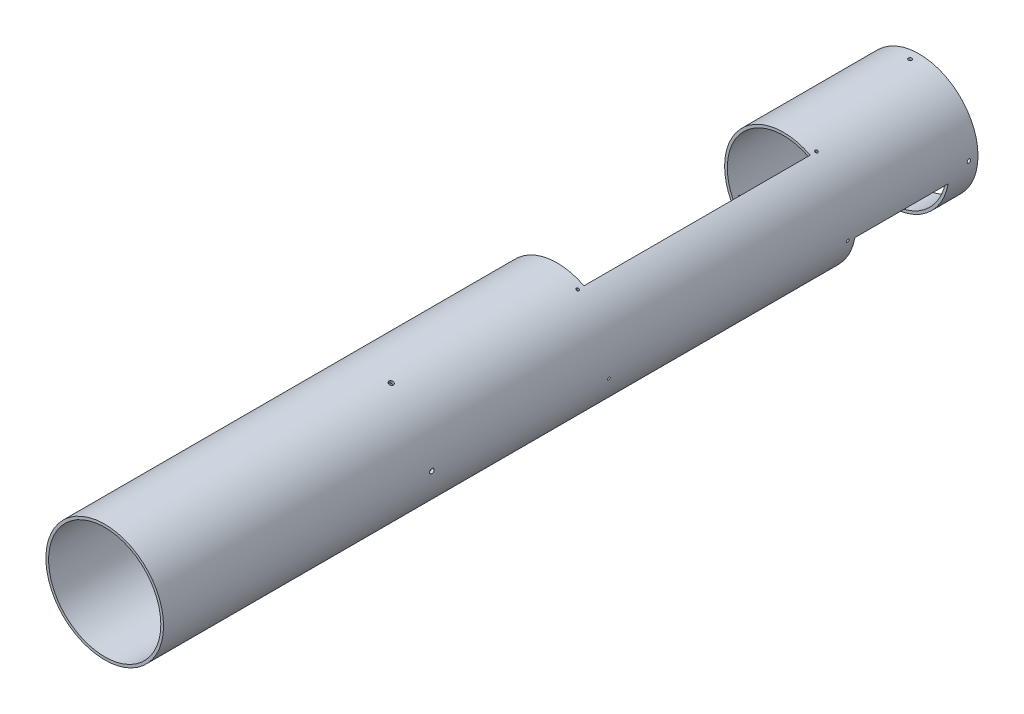
SolidWorks part; units mm, degrees
ref_plane "Front Plane" through (0, 0, 0) normal (0, 0, 1) x (1, 0, 0)
ref_plane "Top Plane" through (0, 0, 0) normal (0, 1, 0) x (1, 0, 0)
ref_plane "Right Plane" through (0, 0, 0) normal (1, 0, 0) x (0, 0, -1)
sketch "Sketch1" plane through (0, 0, 0) normal (0, 0, 1) x (1, 0, 0)
  circle A0 centre (0, 0) radius 62
  circle A1 centre (0, 0) radius 65
  dimension "D1" = 124
  dimension "D2" = 3
extrude "Boss-Extrude1" add sketch "Sketch1" along normal blind 900
sketch "Sketch2" plane through (0, 0, 0) normal (0, 1, 0) x (1, 0, 0)
  line L0 (62, 0) -> (-62, 0) construction
  circle A0 centre (0, -224) radius 1
  circle A1 centre (0, -264) radius 1
  dimension "D1" = 2
  dimension "D3" = 2
  dimension "D2" = 224
  dimension "D4" = 40
ref_plane "Plane1" through (0, 0, 0) normal (-0.7071, 0.7071, 0) x (0.7071, 0.7071, 0)
ref_plane "Plane2" through (-14.1421, 14.1421, 0) normal (-0.7071, 0.7071, 0) x (0.7071, 0.7071, 0)
sketch "Sketch4" plane through (-14.1421, 14.1421, 0) normal (-0.7071, 0.7071, 0) x (0.7071, 0.7071, 0)
  line L0 (-65, 0) -> (-65, -900) construction
  line L1 (-65, -150) -> (65, -150)
  line L2 (-65, -150) -> (-65, -400)
  line L3 (-65, -400) -> (65, -400)
  line L4 (65, -150) -> (65, -400)
  line L5 (65, -900) -> (65, 0) construction
  line L6 (65, 0) -> (-65, 0) construction
  dimension "D1" = 150
  dimension "D2" = 250
extrude "Cut-Extrude4" cut sketch "Sketch4" along normal blind 516
sketch "Sketch5" plane through (0, 0, 0) normal (0, 1, 0) x (1, 0, 0)
  line L0 (-62, 0) -> (62, 0) construction
  circle A0 centre (0, -10) radius 2
  dimension "D1" = 4
  dimension "D2" = 10
extrude "Cut-Extrude5" cut sketch "Sketch5" against normal blind 85
pattern_circular "CirPattern1" count 4 every 90 about axis through (0, 0, 900) along (0, 0, -1) of "Cut-Extrude5"
sketch "Sketch7" plane through (-14.1421, 14.1421, 0) normal (-0.7071, 0.7071, 0) x (0.7071, 0.7071, 0)
  line L0 (-61.8466, -150) -> (61.8466, -150) construction
  line L1 (58.6856, -400) -> (-58.6856, -400) construction
  circle A0 centre (0, -143) radius 1.5
  circle A1 centre (0, -407) radius 1.5
  dimension "D1" = 3
  dimension "D3" = 3
  dimension "D2" = 7
  dimension "D4" = 7
extrude "Cut-Extrude6" cut sketch "Sketch7" along normal blind 243
pattern_circular "CirPattern2" count 5 every 72 about axis through (0, 0, 900) along (0, 0, -1) of "Cut-Extrude6"
sketch "Sketch8" plane through (0, 0, 0) normal (1, 0, 0) x (0, 0, -1)
  line L0 (-900, 65) -> (-900, -65) construction
  circle A0 centre (-603.5, 0) radius 2.5
  dimension "D2" = 5
  dimension "D1" = 296.5
extrude "Cut-Extrude7" cut sketch "Sketch8" along normal blind 209
pattern_circular "CirPattern3" count 5 every 72 about axis through (0, 0, 900) along (0, 0, -1) of "Cut-Extrude7"
ref_plane "Plane3" through (0, 0, 135) normal (0, 0, 1) x (1, 0, 0)
sketch "Sketch9" plane through (0, 0, 135) normal (0, 0, 1) x (1, 0, 0)
  line L0 (-72.0694, 72.0694) -> (72.0694, -72.0694) construction
  line L2 (38.8909, 38.8909) -> (-38.8909, -38.8909) construction
  line L3 (0, 0) -> (11.2871, -64.0125)
  line L4 (1, 0) -> (-1, 0) construction
  line L5 (0, 0) -> (64.0125, -11.2871)
  arc A0 (11.2871, -64.0125) -> (64.0125, -11.2871) centre (0, 0) ccw
  point P6 (0, 0)
  dimension "D1" = 35
extrude "Cut-Extrude8" cut sketch "Sketch9" against normal blind 103
ref_plane "Plane4" through (-14.1421, 14.1421, 0) normal (-0.7071, 0.7071, 0) x (0.7071, 0.7071, 0)
sketch "Sketch11" plane through (-14.1421, 14.1421, 0) normal (-0.7071, 0.7071, 0) x (0.7071, 0.7071, 0)
  line L0 (0, 0) -> (1.5, -407) construction
  circle A0 centre (0, -407) radius 1.5 construction
ref_plane "Plane5" through (0, 0, 0) normal (-0.7071, -0.7071, 0.0037) x (0.0026, 0.0026, 1)
sketch "Sketch12" plane through (0, 0, 0) normal (-0.7071, -0.7071, 0.0037) x (0.0026, 0.0026, 1)
  line L0 (141.499, 65) -> (399.9973, 65) construction
  line L1 (270.7482, 65) -> (270.7482, 0)
  line L3 (270.7482, 149.9397) -> (270.7482, 40.3241) construction
  spline S0 degree 3 poles (188.981, -2.7876) (170.8808, 24.5872) (156.439, 0.5075) (169.623, -11.725) (188.981, -2.7876) (170.8808, 24.5872) (156.439, 0.5075) knots -0.724441 -0.531353 -0.322964 0 0.275559 0.468647 0.677036 1 1.275559 1.468647 1.677036 only from (170.5473, 14.9821) to (170.5473, 14.9821)
  spline S1 degree 1 poles (170.5473, 14.9821) (270.7482, 175.3798) knots 0 0 1 1
  spline S2 degree 3 poles (352.5153, -2.7876) (370.6156, 24.5872) (385.0573, 0.5075) (371.8733, -11.725) (352.5153, -2.7876) (370.6156, 24.5872) (385.0573, 0.5075) knots -0.724441 -0.531353 -0.322964 0 0.275559 0.468647 0.677036 1 1.275559 1.468647 1.677036 only from (370.9491, 14.9821) to (370.9491, 14.9821)
  spline S3 degree 1 poles (370.9491, 14.9821) (270.7482, 175.3798) knots 0 0 1 1
  point P11 (270.7482, 0)
  dimension "D1" = 65
  dimension "D2" = 100.2009
  dimension "D3" = 0
  dimension "D4" = 100.2009
ref_plane "Plane6" through (-123.3067, 124.7178, 270.7463) normal (0.7071, -0.7071, 0) x (-0.7071, -0.7071, 0)
sketch "Sketch15" plane through (-123.3067, 124.7178, 270.7463) normal (0.7071, -0.7071, 0) x (-0.7071, -0.7071, 0)
  circle A0 centre (0, 0) radius 1.5
sketch "Sketch16" plane through (-124.0233, 124.0012, -179.6298) normal (0.7071, -0.7071, 0) x (0.5, 0.5, -0.7071)
  circle A0 centre (0, 0) radius 1.5
ref_plane "Plane7" through (0, 0, 275) normal (0, 0, -1) x (-1, 0, 0)
